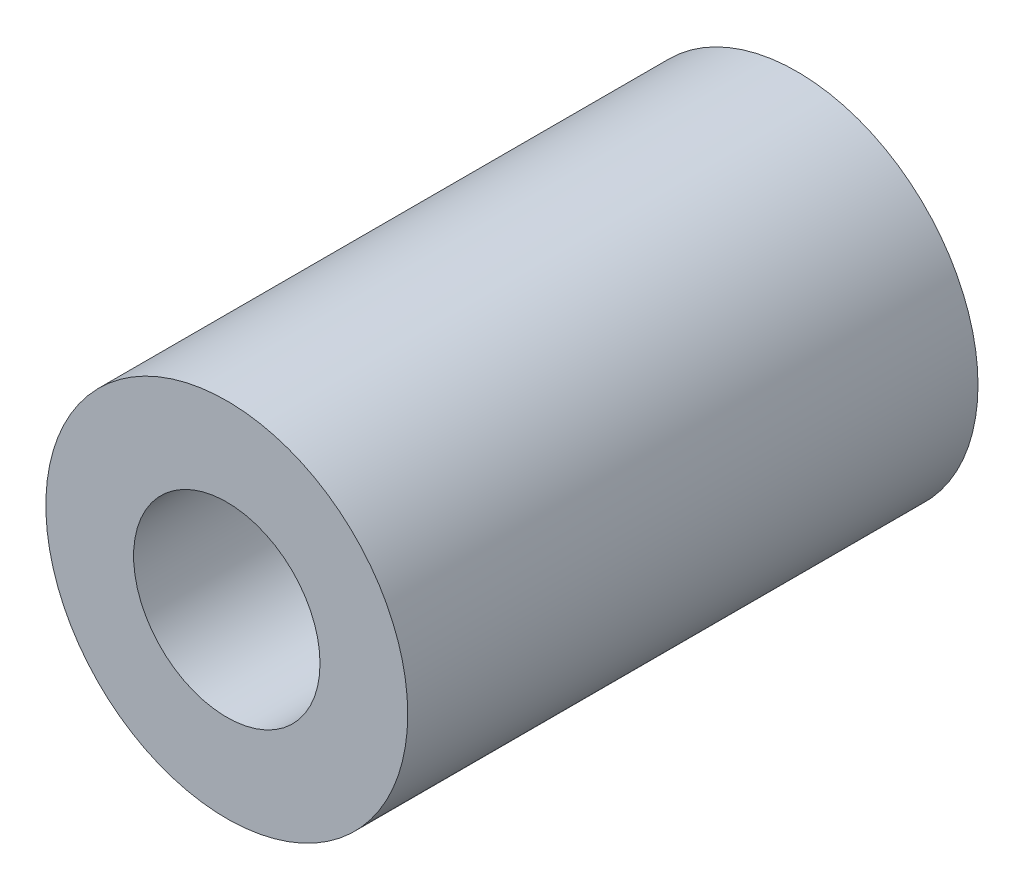
SolidWorks part; units mm, degrees
ref_plane "Front Plane" through (0, 0, 0) normal (0, 0, 1) x (1, 0, 0)
ref_plane "Top Plane" through (0, 0, 0) normal (0, 1, 0) x (1, 0, 0)
ref_plane "Right Plane" through (0, 0, 0) normal (1, 0, 0) x (0, 0, -1)
sketch "Sketch1" plane through (0, 0, 0) normal (0, 0, 1) x (1, 0, 0)
  circle A0 centre (0, 0) radius 3.3
  circle A1 centre (0, 0) radius 1.7
  dimension "D1" = 6.6
  dimension "D2" = 3.4
extrude "Boss-Extrude1" add sketch "Sketch1" along normal blind 10.4
